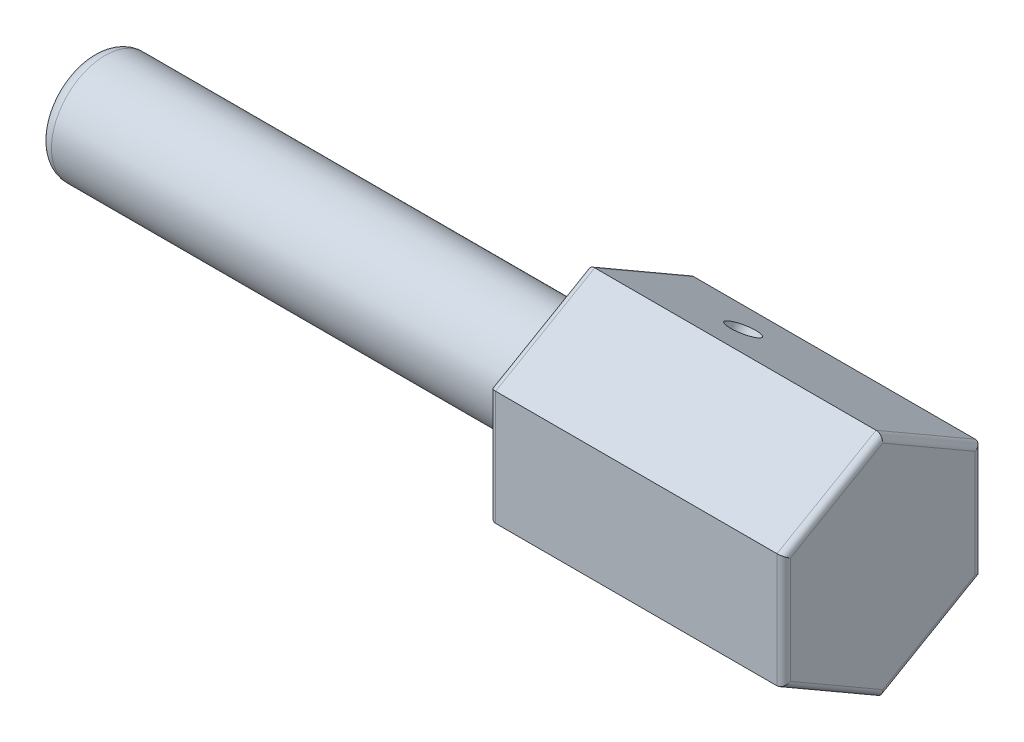
SolidWorks part; units mm, degrees
ref_plane "Alzado" through (0, 0, 0) normal (0, 0, 1) x (1, 0, 0)
ref_plane "Planta" through (0, 0, 0) normal (0, 1, 0) x (1, 0, 0)
ref_plane "Vista lateral" through (0, 0, 0) normal (1, 0, 0) x (0, 0, -1)
sketch "Croquis1" plane through (0, 0, 0) normal (1, 0, 0) x (0, 0, -1)
  circle A0 centre (0, 0) radius 4
  dimension "D1" = 8
extrude "Saliente-Extruir1" add sketch "Croquis1" along normal blind 37.05
sketch "Croquis2" plane through (37.05, 0, 0) normal (1, 0, 0) x (0, 0, -1)
  line L1 (0, -8.5448) -> (7.4, -4.2724)
  line L2 (7.4, -4.2724) -> (7.4, 4.2724)
  line L3 (7.4, 4.2724) -> (0, 8.5448)
  line L4 (0, 8.5448) -> (-7.4, 4.2724)
  line L5 (-7.4, 4.2724) -> (-7.4, -4.2724)
  line L6 (-7.4, -4.2724) -> (0, -8.5448)
  circle A0 centre (0, 0) radius 7.4 construction
  dimension "D1" = 14.8
extrude "Saliente-Extruir2" add sketch "Croquis2" along normal blind 22
fillet "Redondeo1" radius 0.5 13 edges at (37.05, -6.4086, -3.7) (37.05, 0, -7.4) (37.05, 6.4086, -3.7) (37.05, 6.4086, 3.7) (37.05, 0, 7.4) (37.05, -6.4086, 3.7) (37.05, 0, -4) (59.05, 0, 7.4) (59.05, 6.4086, 3.7) (59.05, 6.4086, -3.7) (59.05, 0, -7.4) (59.05, -6.4086, -3.7) (59.05, -6.4086, 3.7)
fillet "Redondeo2" radius 1 1 edges at (0, 0, -4)
sketch "Croquis3" plane through (0, 6.4086, -3.7) normal (0, 0.866, -0.5) x (1, 0, 0)
  line L1 (37.55, 4.2724) -> (37.55, -4.2724) construction
  circle A0 centre (44.925, 0) radius 1.1
  point P2 (37.55, 0)
  dimension "D2" = 2.2
  dimension "D1" = 7.375
extrude "Cortar-Extruir1" cut sketch "Croquis3" against normal blind 20 contours A0
